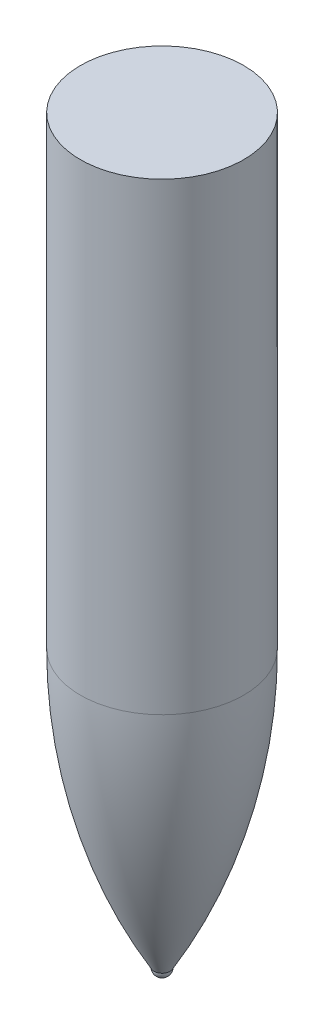
SolidWorks part; units mm, degrees
ref_plane "Front Plane" through (0, 0, 0) normal (0, 0, 1) x (1, 0, 0)
ref_plane "Top Plane" through (0, 0, 0) normal (0, 1, 0) x (1, 0, 0)
ref_plane "Right Plane" through (0, 0, 0) normal (1, 0, 0) x (0, 0, -1)
sketch "Sketch1" plane through (0, 0, 0) normal (0, 0, 1) x (1, 0, 0)
  line L0 (0, 0) -> (0, 50.0664) construction
  line L1 (-2.5, 22.9) -> (-2.5, 8.6954)
  line L2 (-10.2143, 12.9) -> (7.6986, 12.9) construction
  line L3 (-2.5, 22.9) -> (0, 22.9)
  line L4 (0, 0) -> (0, 22.9)
  arc A0 (-2.5, 8.6954) -> (-0.2426, 0.2429) centre (14.4531, 8.6954) ccw
  arc A1 (-0.2426, 0.2429) -> (0, 0) centre (0, 0.2426) ccw
  point P10 (-0.3403, 0.941)
  point P12 (-0.3545, 0.3371)
  point P13 (-0.2426, 0.2426)
  dimension "D1" = 12.9
  dimension "D2" = 10
  dimension "D3" = 4.2046
  dimension "D4" = 2.5
revolve "Revolve1" add sketch "Sketch1" angle 360 about L4
